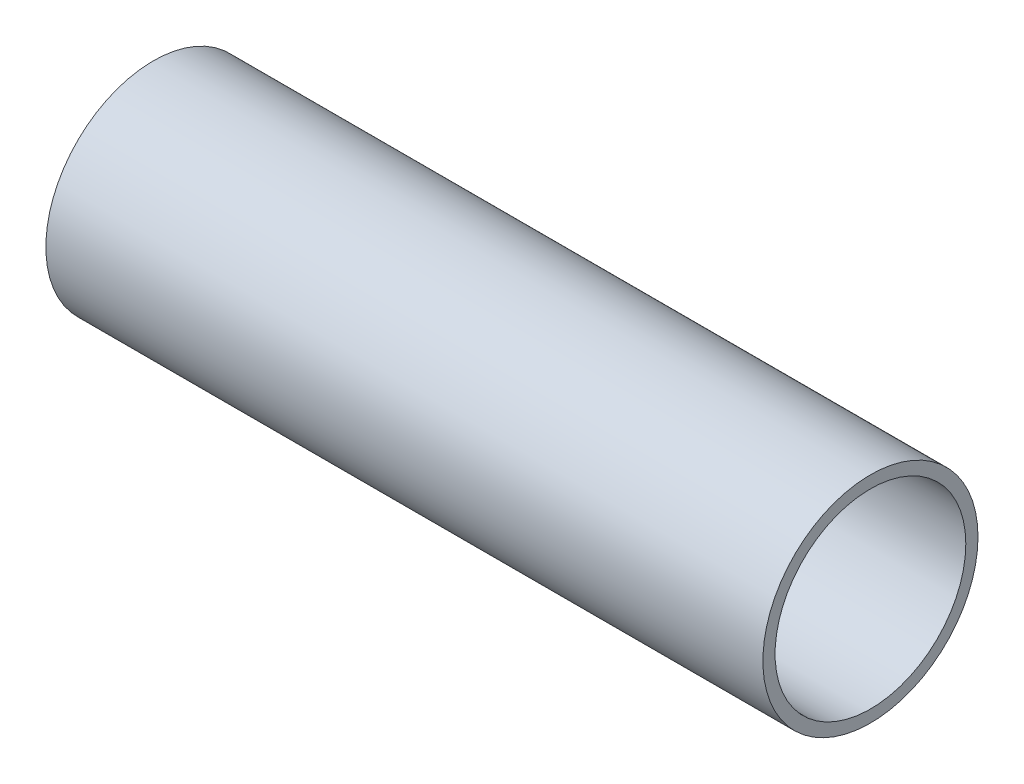
SolidWorks part; units mm, degrees
ref_plane "Plan de face" through (0, 0, 0) normal (0, 0, 1) x (1, 0, 0)
ref_plane "Plan de dessus" through (0, 0, 0) normal (0, 1, 0) x (1, 0, 0)
ref_plane "Plan de droite" through (0, 0, 0) normal (1, 0, 0) x (0, 0, -1)
sketch "Sketch1" plane through (0, 0, 0) normal (1, 0, 0) x (0, 0, -1)
  circle A0 centre (0, 0) radius 15
  circle A1 centre (0, 0) radius 13.3
  dimension "D1" = 26.6
  dimension "D2" = 30
  dimension "D3" = 1.7
extrude "Extrude1" add sketch "Sketch1" along normal blind 100
